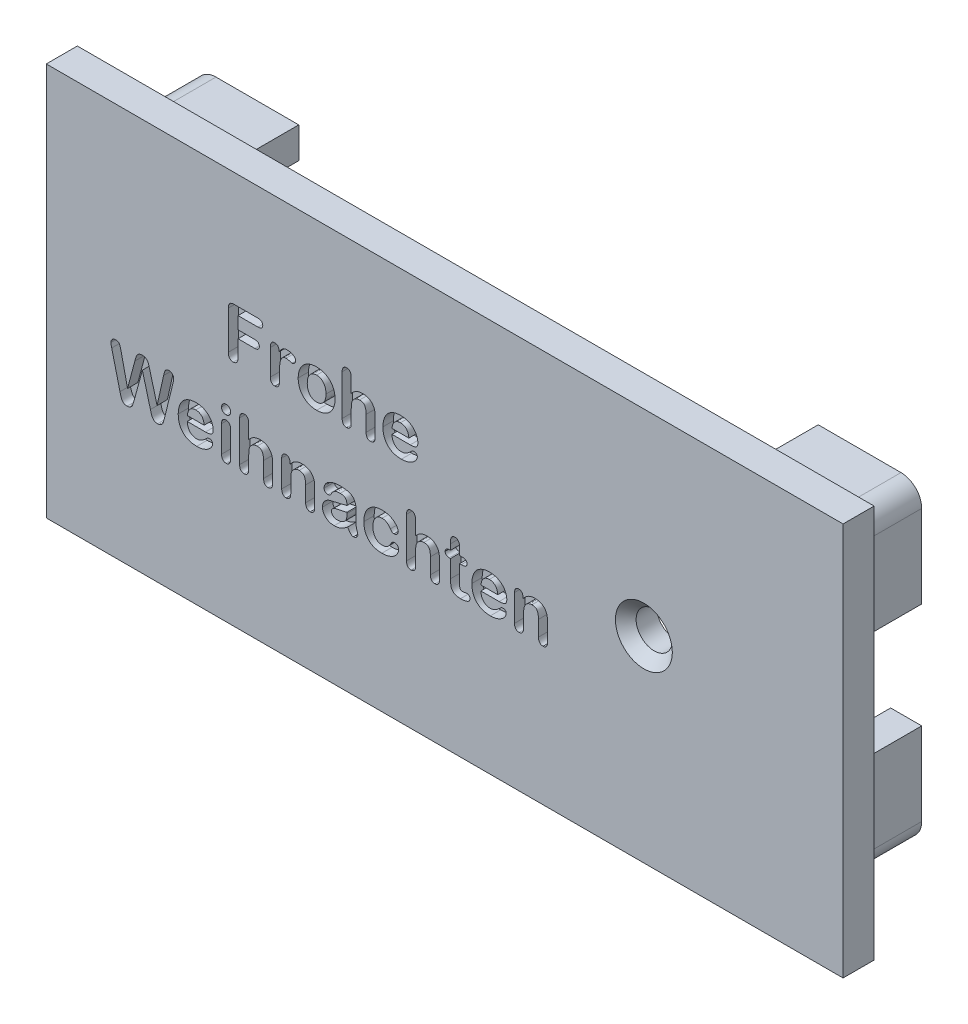
SolidWorks part; units mm, degrees
ref_plane "Ebene vorne" through (0, 0, 0) normal (0, 0, 1) x (1, 0, 0)
ref_plane "Ebene oben" through (0, 0, 0) normal (0, 1, 0) x (1, 0, 0)
ref_plane "Ebene rechts" through (0, 0, 0) normal (1, 0, 0) x (0, 0, -1)
sketch "Skizze1" plane through (0, 0, 0) normal (0, 0, 1) x (1, 0, 0)
  line L1 (-35.5, -15.5) -> (35.5, -15.5)
  line L2 (-35.5, -15.5) -> (-35.5, 15.5)
  line L3 (-35.5, 15.5) -> (35.5, 15.5)
  line L4 (35.5, -15.5) -> (35.5, 15.5)
  line L5 (-35.5, -15.5) -> (35.5, 15.5) construction
  line L6 (-35.5, 15.5) -> (35.5, -15.5) construction
  point P0 (0, 0)
  dimension "D1" = 71
  dimension "D2" = 31
sketch "Skizze4" plane through (0, 0, 0) normal (0, 0, 1) x (1, 0, 0)
  line L0 (-35.5, -15.5) -> (35.5, 15.5) construction
  line L1 (38.5, -19) -> (-38.5, -19)
  line L2 (38.5, -19) -> (38.5, 19)
  line L3 (38.5, 19) -> (-38.5, 19)
  line L4 (-38.5, -19) -> (-38.5, 19)
  line L5 (38.5, -19) -> (-38.5, 19) construction
  line L6 (38.5, 19) -> (-38.5, -19) construction
  line L7 (0, 0) -> (19.25, 0) construction
  line L8 (19.25, 0) -> (38.5, 0) construction
  circle A0 centre (19.25, 0) radius 1.75
  point P0 (0, 0)
  dimension "D3" = 3.5
  dimension "D1" = 77
  dimension "D2" = 38
extrude "Aufsatz-Linear austragen1" add sketch "Skizze4" along normal blind 3
sketch "Skizze5" plane through (0, 0, 0) normal (0, 0, -1) x (-1, 0, 0)
  line L0 (-35.1, 5.1) -> (-35.1, 15.1)
  line L1 (-35.1, 15.1) -> (-25.1, 15.1)
  line L2 (-25.1, 15.1) -> (-25.1, 12.1)
  line L3 (-25.1, 12.1) -> (-32.1, 12.1)
  line L4 (-32.1, 12.1) -> (-32.1, 5.1)
  line L5 (-32.1, 5.1) -> (-35.1, 5.1)
  line L6 (35.5, 15.5) -> (-35.5, 15.5) construction
  line L7 (-35.5, -15.5) -> (-35.5, 15.5) construction
  line L8 (0, 0) -> (0, 15.5) construction
  line L9 (35.5, -15.5) -> (-35.5, 15.5) construction
  line L10 (-35.5, 0) -> (35.5, 0) construction
  line L11 (35.5, -15.5) -> (35.5, 15.5) construction
  line L12 (32.1, 12.1) -> (32.1, 5.1)
  line L13 (25.1, 12.1) -> (32.1, 12.1)
  line L14 (25.1, 15.1) -> (25.1, 12.1)
  line L15 (35.1, 15.1) -> (25.1, 15.1)
  line L16 (35.1, 5.1) -> (35.1, 15.1)
  line L17 (32.1, 5.1) -> (35.1, 5.1)
  line L18 (25.1, -12.1) -> (32.1, -12.1)
  line L19 (25.1, -15.1) -> (25.1, -12.1)
  line L20 (35.1, -15.1) -> (25.1, -15.1)
  line L21 (35.1, -5.1) -> (35.1, -15.1)
  line L22 (32.1, -5.1) -> (35.1, -5.1)
  line L23 (32.1, -12.1) -> (32.1, -5.1)
  line L24 (-32.1, -12.1) -> (-32.1, -5.1)
  line L25 (-25.1, -12.1) -> (-32.1, -12.1)
  line L26 (-25.1, -15.1) -> (-25.1, -12.1)
  line L27 (-35.1, -15.1) -> (-25.1, -15.1)
  line L28 (-35.1, -5.1) -> (-35.1, -15.1)
  line L29 (-32.1, -5.1) -> (-35.1, -5.1)
  dimension "D1" = 3
  dimension "D2" = 10
  dimension "D3" = 0.4
  dimension "D4" = 0.4
extrude "Aufsatz-Linear austragen2" add sketch "Skizze5" along normal blind 8
sketch "Skizze6" plane through (0, 0, 0) normal (0, 0, -1) x (-1, 0, 0)
  line L0 (-25.287, 1.6176) -> (-27.2189, 2.1353)
  line L1 (-21.3853, 7.9689) -> (-20.8676, 6.037)
  line L2 (-20.8676, 6.037) -> (-19.25, 0) construction
  line L3 (-19.25, 0) -> (-25.287, 1.6176) construction
  line L4 (-20.4874, -1.2374) -> (-18.0126, 1.2374) construction
  line L5 (-20.4874, 1.2374) -> (-18.0126, -1.2374) construction
  line L6 (-11.2811, -2.1353) -> (-13.213, -1.6176)
  line L7 (-14.8306, 4.4194) -> (-13.4164, 5.8336)
  line L8 (-25.0836, -5.8336) -> (-23.6694, -4.4194)
  line L9 (-17.6324, -6.037) -> (-17.1147, -7.9689)
  line L10 (-38.5, -19) -> (-38.5, 19) construction
  arc A0 (-25.287, 1.6176) -> (-20.8676, 6.037) centre (-19.25, 0) cw
  arc A1 (-27.2189, 2.1353) -> (-21.3853, 7.9689) centre (-19.25, 0) cw
  circle A2 centre (-19.25, 0) radius 1.75 construction
  arc A3 (-14.8306, 4.4194) -> (-13.213, -1.6176) centre (-19.25, 0) cw
  arc A4 (-13.4164, 5.8336) -> (-11.2811, -2.1353) centre (-19.25, 0) cw
  arc A5 (-17.6324, -6.037) -> (-23.6694, -4.4194) centre (-19.25, 0) cw
  arc A6 (-17.1147, -7.9689) -> (-25.0836, -5.8336) centre (-19.25, 0) cw
  point P12 (-18.0147, -6.3979)
  point P23 (-19.25, 0)
  dimension "D2" = 6.25
  dimension "D1" = 2
  dimension "D3" = 3
  dimension "D4" = 60
  dimension "D5" = 45
extrude "Aufsatz-Linear austragen3" add sketch "Skizze6" along normal blind 4
fillet "Verrundung1" radius 2 8 edges at (-32.1, -12.1, -4) (-32.1, 12.1, -4) (32.1, 12.1, -4) (32.1, -12.1, -4) (35.1, -15.1, -4) (-35.1, -15.1, -4) (-35.1, 15.1, -4) (35.1, 15.1, -4)
fillet "Verrundung3" radius 0.75 6 edges at (23.6694, -4.4194, -2) (17.6324, -6.037, -2) (13.213, -1.6176, -2) (14.8306, 4.4194, -2) (20.8676, 6.037, -2) (25.287, 1.6176, -2)
chamfer "Fase2" distance 1 angle 45 1 edges at (21, 0, 3)
sketch "Skizze7" plane through (0, 0, 3) normal (0, 0, 1) x (1, 0, 0)
  line L0 (-35.5, 3.1406) -> (13.5, 3.1406) construction
  line L4 (-35.5, -15.5) -> (-35.5, 15.5) construction
  line L6 (13.5, 3.1406) -> (13.5, -19) construction
  line L7 (-38.5, -19) -> (38.5, -19) construction
  line L8 (16.5, 0) -> (13.5, 0) construction
  circle A0 centre (19.25, 0) radius 2.75 construction
  text T0 "Frohe \r\nWeihnachten" font "Arial Rounded MT Bold" height 5
  point P15 (-35.5, 3.6989)
  point P16 (-35.5, 3.1406)
  dimension "D1" = 3
extrude "Schnitt-Linear austragen1" cut sketch "Skizze7" against normal blind 1
